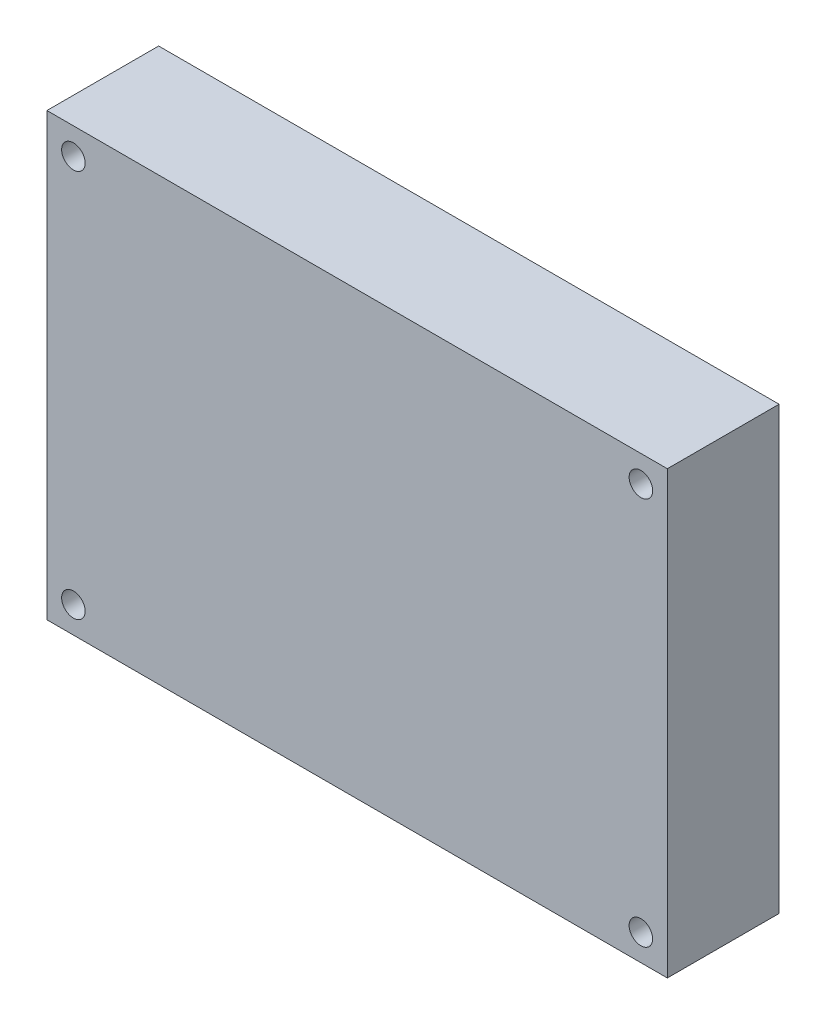
SolidWorks part; units mm, degrees
ref_plane "Plan de face" through (0, 0, 0) normal (0, 0, 1) x (1, 0, 0)
ref_plane "Plan de dessus" through (0, 0, 0) normal (0, 1, 0) x (1, 0, 0)
ref_plane "Plan de droite" through (0, 0, 0) normal (1, 0, 0) x (0, 0, -1)
sketch "Esquisse1" plane through (0, 0, 0) normal (0, 0, 1) x (1, 0, 0)
  line L1 (-52.75, -37.5) -> (52.75, -37.5)
  line L2 (-52.75, -37.5) -> (-52.75, 37.5)
  line L3 (-52.75, 37.5) -> (52.75, 37.5)
  line L4 (52.75, -37.5) -> (52.75, 37.5)
  line L5 (-52.75, -37.5) -> (52.75, 37.5) construction
  line L6 (-52.75, 37.5) -> (52.75, -37.5) construction
  point P0 (0, 0)
  dimension "D1" = 75
  dimension "D2" = 105.5
extrude "Boss.-Extru.1" add sketch "Esquisse1" along normal blind 19
sketch "Esquisse2" plane through (0, 0, 19) normal (0, 0, 1) x (1, 0, 0)
  line L0 (52.75, 37.5) -> (-52.75, 37.5) construction
  line L1 (-52.75, 37.5) -> (-52.75, -37.5) construction
  circle A0 centre (-48.25, 33) radius 2
  dimension "D1" = 4
  dimension "D2" = 4.5
  dimension "D3" = 4.5
extrude "Enlèv. mat.-Extru.1" cut sketch "Esquisse2" against normal through all
mirror "Symétrie1" about plane through (0, 0, 0) normal (0, 1, 0) of "Enlèv. mat.-Extru.1"
mirror "Symétrie2" about plane through (0, 0, 0) normal (1, 0, 0) of "Symétrie1", "Enlèv. mat.-Extru.1"
